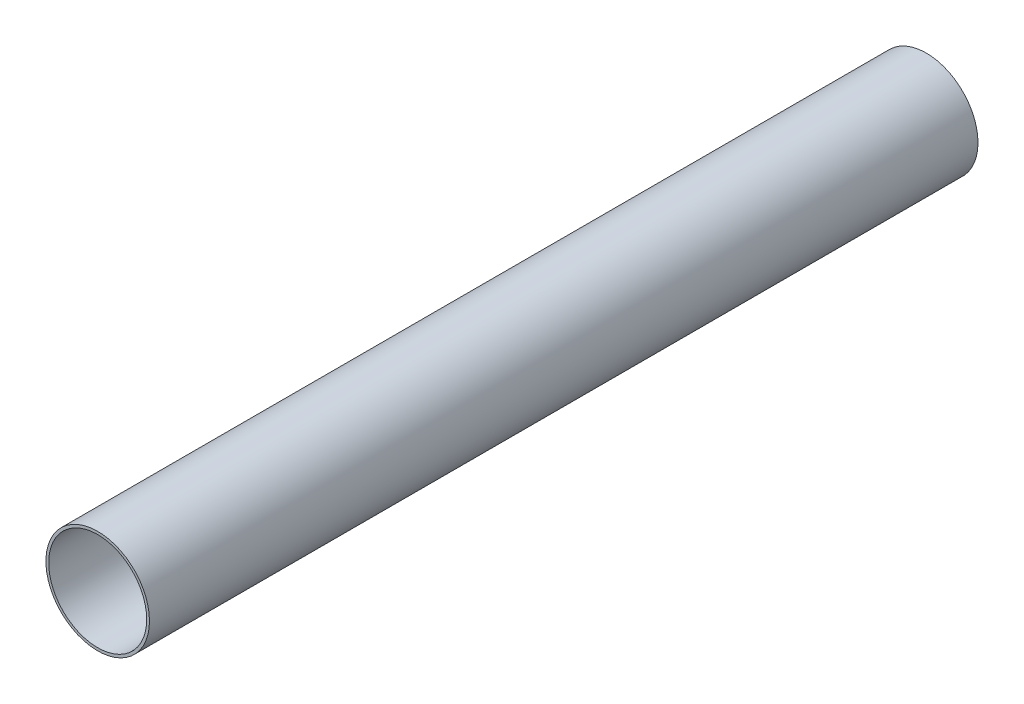
SolidWorks part; units mm, degrees
ref_plane "Front Plane" through (0, 0, 0) normal (0, 0, 1) x (1, 0, 0)
ref_plane "Top Plane" through (0, 0, 0) normal (0, 1, 0) x (1, 0, 0)
ref_plane "Right Plane" through (0, 0, 0) normal (1, 0, 0) x (0, 0, -1)
sketch "Sketch1" plane through (0, 0, 0) normal (0, 0, 1) x (1, 0, 0)
  circle A0 centre (0, 0) radius 37.5
  circle A1 centre (0, 0) radius 35.5
  dimension "D1" = 71
  dimension "D2" = 75
extrude "Boss-Extrude1" add sketch "Sketch1" along normal blind 600
